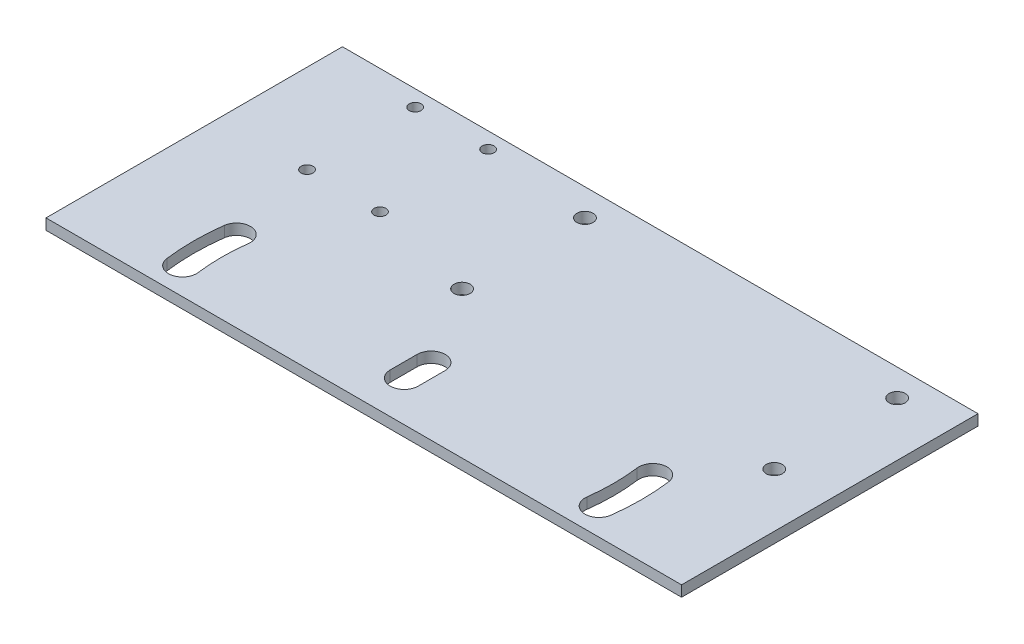
SolidWorks part; units mm, degrees
ref_plane "前视基准面" through (0, 0, 0) normal (0, 0, 1) x (1, 0, 0)
ref_plane "上视基准面" through (0, 0, 0) normal (0, 1, 0) x (1, 0, 0)
ref_plane "右视基准面" through (0, 0, 0) normal (1, 0, 0) x (0, 0, -1)
sketch "草图1" plane through (0, 0, 0) normal (0, 1, 0) x (1, 0, 0)
  line L0 (0, -13) -> (30, -13) construction
  line L1 (0, 0) -> (117.92, 0)
  line L2 (0, 0) -> (0, -55)
  line L3 (0, -55) -> (117.92, -55)
  line L4 (117.92, 0) -> (117.92, -55)
  line L5 (30, -23.03) -> (30, -2.97) construction
  line L6 (16.46, -23.03) -> (16.46, -2.97) construction
  line L7 (50, -5) -> (50, -27.8) construction
  line L8 (107.92, -5) -> (107.92, -27.8) construction
  line L9 (30, -2.97) -> (16.46, -2.97) construction
  line L10 (23.23, -2.97) -> (23.23, -23.03) construction
  line L11 (16.46, -23.03) -> (30, -23.03) construction
  line L12 (50, -16.4) -> (107.92, -16.4) construction
  line L13 (50, -5) -> (107.92, -5) construction
  line L14 (78.96, -5) -> (78.96, -27.8) construction
  line L15 (50, -27.8) -> (107.92, -27.8) construction
  line L16 (58.96, -55) -> (58.96, -45) construction
  line L17 (20, -45) -> (97.92, -45) construction
  line L18 (58.96, -45) -> (100.1763, -50.3337) construction
  line L19 (56.36, -47.5) -> (56.36, -42.5)
  line L20 (61.56, -47.5) -> (61.56, -42.5)
  circle A0 centre (16.46, -2.97) radius 1.1
  circle A1 centre (30, -2.97) radius 1.1
  circle A2 centre (30, -23.03) radius 1.1
  circle A3 centre (16.46, -23.03) radius 1.1
  circle A4 centre (50, -5) radius 1.5
  circle A5 centre (107.92, -5) radius 1.5
  circle A6 centre (107.92, -27.8) radius 1.5
  circle A7 centre (50, -27.8) radius 1.5
  circle A8 centre (58.96, -45) radius 2.6 construction
  circle A9 centre (97.92, -45) radius 2.6 construction
  arc A10 (95.0193, -40.3337) -> (95.0193, -49.6663) centre (58.96, -45) cw
  arc A11 (100.1763, -39.6663) -> (100.1763, -50.3337) centre (58.96, -45) cw
  arc A12 (95.0193, -49.6663) -> (100.1763, -50.3337) centre (97.5978, -50) ccw
  arc A13 (95.0193, -40.3337) -> (100.1763, -39.6663) centre (97.5978, -40) cw
  circle A14 centre (20, -45) radius 2.6 construction
  arc A15 (22.9007, -40.3337) -> (17.7437, -39.6663) centre (20.3222, -40) ccw
  arc A16 (22.9007, -49.6663) -> (17.7437, -50.3337) centre (20.3222, -50) cw
  arc A17 (17.7437, -39.6663) -> (17.7437, -50.3337) centre (58.96, -45) ccw
  arc A18 (22.9007, -40.3337) -> (22.9007, -49.6663) centre (58.96, -45) ccw
  arc A19 (56.36, -42.5) -> (61.56, -42.5) centre (58.96, -42.5) cw
  arc A20 (56.36, -47.5) -> (61.56, -47.5) centre (58.96, -47.5) ccw
  point P10 (30, -13)
  point P13 (16.46, -13)
  point P38 (58.96, -45)
  point P52 (95.32, -45)
  point P53 (100.52, -45)
  point P57 (56.36, -45)
  point P61 (56.36, -41.5295)
  dimension "D3" = 2.2
  dimension "D10" = 3
  dimension "D14" = 5.2
  dimension "D16" = 5.2
  dimension "D1" = 117.92
  dimension "D2" = 55
  dimension "D4" = 13.54
  dimension "D5" = 20.06
  dimension "D6" = 13
  dimension "D7" = 16.46
  dimension "D8" = 22.8
  dimension "D9" = 57.92
  dimension "D11" = 10
  dimension "D12" = 5
  dimension "D13" = 10
  dimension "D15" = 20
  dimension "D17" = 5
  dimension "D18" = 5
extrude "凸台-拉伸1" add sketch "草图1" along normal blind 2
